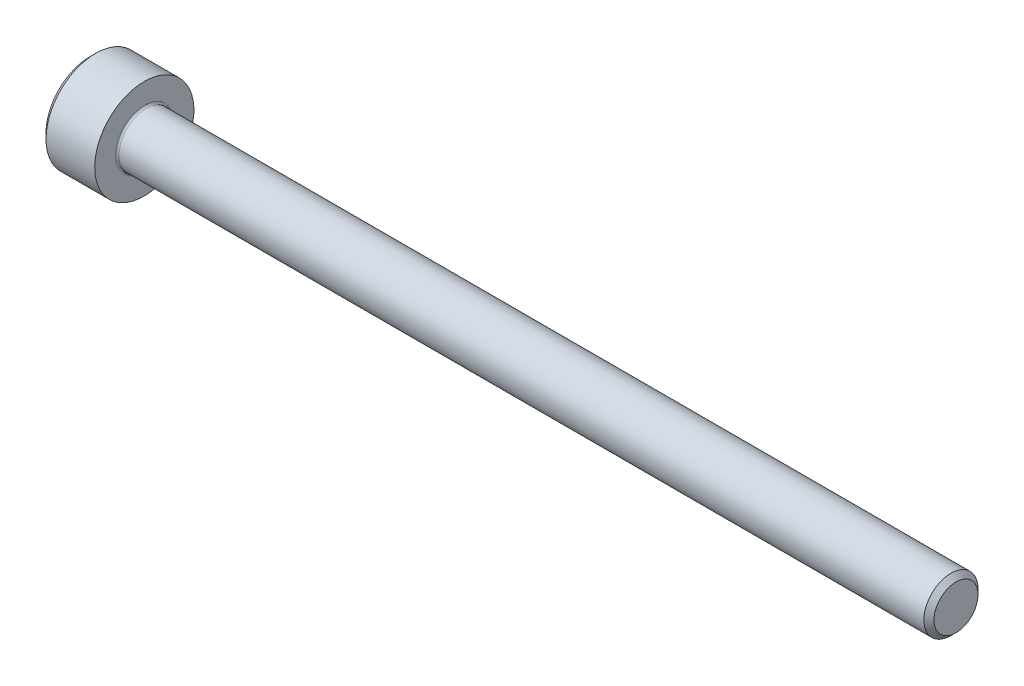
SolidWorks part; units mm, degrees
revolve "Base-Revolve" add sketch "BodySke"
sketch "BodySke" plane through (0, 0, 0) normal (0, 0, 1) x (1, 0, 0)
  line L0 (0, 0) -> (0, 2.45)
  line L1 (0.3, 2.75) -> (3, 2.75)
  line L2 (3, 2.75) -> (3, 1.5)
  line L3 (3, 1.5) -> (47.7195, 1.5)
  line L4 (48, 1.2195) -> (48, 0)
  line L5 (48, 0) -> (0, 0)
  line L6 (-31.75, 0) -> (127, 0) construction
  line L7 (0, 2.45) -> (0.3, 2.75)
  line L8 (48, 1.2195) -> (47.7195, 1.5)
  line L9 (0, -2.45) -> (0.3, -2.75) construction
  line L10 (48, -1.2195) -> (47.7195, -1.5) construction
  line L11 (3.5, 9.525) -> (3.5, 3.175) construction
  line L12 (30, 9.525) -> (30, 3.175) construction
  line L13 (-2, 9.525) -> (-2, 3.175) construction
  dimension "Diameter" = 3
  dimension "Head_ht" = 3
  dimension "Length" = 45
  dimension "Body_ch_ang" = 45
  dimension "Head_dia" = 5.5
  dimension "Head_ch_ang" = 45
  dimension "Minor_dia" = 2.439
  dimension "Advance" = 0.5
  dimension "Thread_nom" = 18
  dimension "Thread_length" = 50
  dimension "Head_ch_ht" = 0.3
cosmetic thread "ThreadCosmetic" [suppressed]
fillet "Fillet1" radius 0.1 1 edges at (3, 0, 1.5)
ref_plane "Plane1" through (0, 0, 0) normal (0, 0, 1) x (1, 0, 0)
ref_plane "Plane2" through (0, 0, 0) normal (0, 1, 0) x (1, 0, 0)
ref_plane "Plane3" through (0, 0, 0) normal (1, 0, 0) x (0, 0, -1)
other "Configuration Table"
sketch "Sketch2" plane through (0, 0, 0) normal (0, 0, 1) x (1, 0, 0)
  line L0 (0, 1.28) -> (1.3, 1.28)
  line L1 (1.3, 1.28) -> (2.039, 0)
  line L2 (-31.75, 0) -> (127, 0) construction
  line L3 (2.039, 0) -> (0, 0)
  line L4 (0, 0) -> (0, 1.28)
  line L5 (0, 2.45) -> (0, -2.45) construction
  line L6 (0, 0) -> (47.625, 0) construction
  line L7 (3, -2.75) -> (3, 2.75) construction
  dimension "D1" = 1.28
  dimension "D2" = 60
revolve "Hex-PreBroach" cut sketch "Sketch2" angle 360 about L6
sketch "Sketch3" plane through (0, 0, 0) normal (-1, 0, 0) x (0, 0.5, 0.866)
  line L0 (0.739, 1.28) -> (-0.739, 1.28)
  line L1 (-0.739, 1.28) -> (-1.478, 0)
  line L2 (0.739, 1.28) -> (1.478, 0)
  line L3 (0.739, -1.28) -> (1.478, 0)
  line L4 (0.739, -1.28) -> (-0.739, -1.28)
  line L5 (-0.739, -1.28) -> (-1.478, 0)
  dimension "D1" = 1.28
  dimension "D2" = 1.28
  dimension "Hex_size" = 2.56
extrude "Hex" cut sketch "Sketch3" against normal blind 1.3
sketch "Sketch4" plane through (0, 0, 0) normal (-1, 0, 0) x (0, 0, 1)
  line L0 (0, 0) -> (1.4605, 0)
  line L1 (0, 0) -> (6.1484, 3.5498) construction
  line L2 (0, 0) -> (0.7302, 1.2648)
  line L3 (1.2009, 0.3267) -> (1.3933, 0.4378)
  line L4 (0.8834, 0.8767) -> (1.0758, 0.9877)
  arc A0 (1.2009, 0.3267) -> (0.8834, 0.8767) centre (0, 0) ccw
  arc A1 (1.4605, 0) -> (1.3933, 0.4378) centre (0, 0) ccw
  arc A2 (0.7302, 1.2648) -> (1.0758, 0.9877) centre (0, 0) cw
  dimension "D1" = 30
  dimension "D2" = 60
  dimension "Spline_p_dim" = 0.635
  dimension "D3" = 0.3175
extrude "Spline" [suppressed] cut sketch "Sketch4" against normal blind 1.3
pattern_circular "CirPattern1" [suppressed] count 6 every 60
sketch "Sketch5" plane through (0, 0, 0) normal (0, 0, 1) x (1, 0, 0)
  line L0 (-31.75, 0) -> (127, 0) construction
  line L2 (0, 2.45) -> (0, -2.45) construction
  circle A0 centre (1.2, 0) radius 0.475
  dimension "Drilled_hole_dia" = 0.95
  dimension "Drilled_hole_loc" = 1.2
extrude "Hole" [suppressed] cut sketch "Sketch5" against normal through all and the other way through all
pattern_circular "Drilled-4" [suppressed] count 2 every 60
pattern_circular "Drilled-6" [suppressed] count 3 every 60
sketch "ThdSchSke" plane through (0, 0, 0) normal (0, 0, 1) x (1, 0, 0)
  line L0 (30, -1.2195) -> (29.8036, -1.5)
  line L1 (30, -1.2195) -> (30.1964, -1.5)
  line L2 (30.1964, -1.5) -> (30.1964, -1.875)
  line L3 (-3.175, 0) -> (5.1513, 0) construction
  line L5 (30.1964, -1.875) -> (29.8036, -1.875)
  line L6 (29.8036, -1.875) -> (29.8036, -1.5)
  line L7 (0, 2.45) -> (0, -2.45) construction
  dimension "Thread_minor" = 2.439
  dimension "Diameter" = 3
revolve "ThreadSchematic" [suppressed] cut sketch "ThdSchSke" angle 360 about L3
pattern_linear "ThdSchPat" [suppressed]
equation "\"D2@Sketch3\" = \"Hex_size@Sketch3\" / 2"
equation "\"D1@Sketch3\" = \"Hex_size@Sketch3\" / 2"
equation "\"D1@Sketch2\" = \"Hex_size@Sketch3\" / 2"
equation "\"D3@Sketch4\" = \"Spline_p_dim@Sketch4\" / 2"
equation "\"Thread_minor@ThreadCosmetic\"  =  \"Minor_dia@BodySke\""
equation "\"D2@CirPattern1\" = 360 / \"Num_teeth@CirPattern1\""
equation "\"Wall_thickness@Sketch2\" = \"Head_ht@BodySke\" - \"Key_eng@Hex\""
equation "\"Thread_length@ThreadCosmetic\" = ((sgn( (\"Length@BodySke\" - \"Advance@BodySke\" ) - \"Thread_nom@BodySke\" )-1)*( (\"Length@BodySke\" - \"Advance@BodySke\" ) - \"Thread_nom@BodySke\" ))/-2+ \"Thread_nom@BodySke\""
equation "\"Thread_minor@ThdSchSke\" = \"Minor_dia@BodySke\""
equation "\"Diameter@ThdSchSke\" = \"Diameter@BodySke\""
equation "\"Overcut@ThdSchSke\" = \"Diameter@BodySke\" * 1.25"
equation "\"Start@ThdSchSke\" = \"Head_ht@BodySke\" + \"Length@BodySke\" - \"Thread_length@ThreadCosmetic\"  '---Non-countersunk---"
equation "\"Num_threads@ThdSchPat\" = int( \"Thread_length@ThreadCosmetic\" / \"Advance@BodySke\" + 0.999 )  + 1"
equation "\"Advance@ThdSchPat\" = \"Thread_length@ThreadCosmetic\" /  (\"Num_threads@ThdSchPat\" - 1) 'relax it"
equation "\"Num_threads@ThdSchPat\" = \"Num_threads@ThdSchPat\" - sgn( \"Num_threads@ThdSchPat\" - 1) '---chamfered tips only---"
